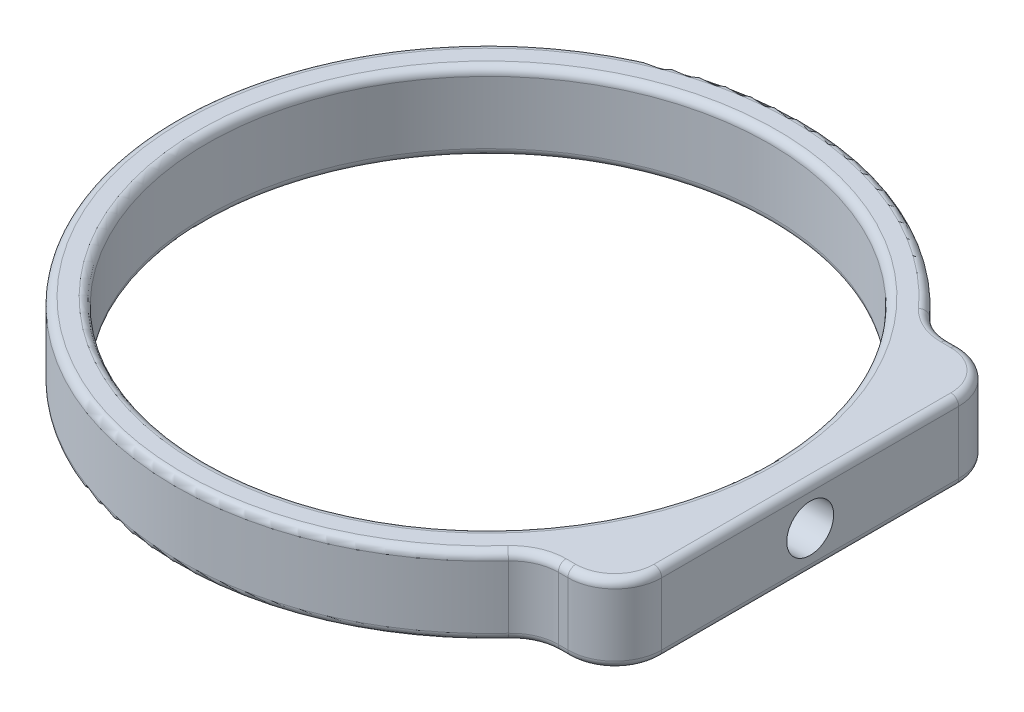
SolidWorks part; units mm, degrees
ref_plane "Plan de face" through (0, 0, 0) normal (0, 0, 1) x (1, 0, 0)
ref_plane "Plan de dessus" through (0, 0, 0) normal (0, 1, 0) x (1, 0, 0)
ref_plane "Plan de droite" through (0, 0, 0) normal (1, 0, 0) x (0, 0, -1)
sketch "Esquisse1" plane through (0, 0, 0) normal (0, 1, 0) x (1, 0, 0)
  line L0 (7.8062, 6.25) -> (10.3062, 6.25)
  line L1 (10.3062, 6.25) -> (10.3062, -6.25)
  line L2 (10.3062, -6.25) -> (7.8062, -6.25)
  circle A0 centre (0, 0) radius 9
  arc A1 (7.8062, 6.25) -> (7.8062, -6.25) centre (0, 0) ccw
  point P11 (10.3062, 0)
  dimension "D1" = 18
  dimension "D3" = 1
  dimension "D2" = 2.5
  dimension "D4" = 12.5
extrude "Boss.-Extru.1" add sketch "Esquisse1" along normal blind 2.5
sketch "Esquisse2" plane through (10.3062, 0, 0) normal (1, 0, 0) x (0, 0, -1)
  line L0 (-6.25, 0) -> (6.25, 2.5) construction
  circle A0 centre (0, 1.25) radius 0.75
  dimension "D1" = 1.5
extrude "Enlèv. mat.-Extru.1" cut sketch "Esquisse2" against normal up to surface (1.3376 mm away)
fillet "Congé1" radius 1.5 4 edges at (10.3062, 1.25, 6.25) (7.8062, 1.25, 6.25) (10.3062, 1.25, -6.25) (7.8062, 1.25, -6.25)
fillet "Congé2" radius 0.25 18 edges at (0, 2.5, 9) (7.8906, 2.5, 6.3777) (-10, 2.5, 0) (7.8906, 2.5, -6.3777) (8.6513, 2.5, -6.25) (9.8669, 2.5, -5.8107) (10.3062, 2.5, 0) (9.8669, 2.5, 5.8107) (8.6513, 2.5, 6.25) (0, 0, 9) (9.8669, 0, -5.8107) (8.6513, 0, -6.25) (7.8906, 0, -6.3777) (-10, 0, 0) (7.8906, 0, 6.3777) (8.6513, 0, 6.25) (9.8669, 0, 5.8107) (10.3062, 0, 0)
